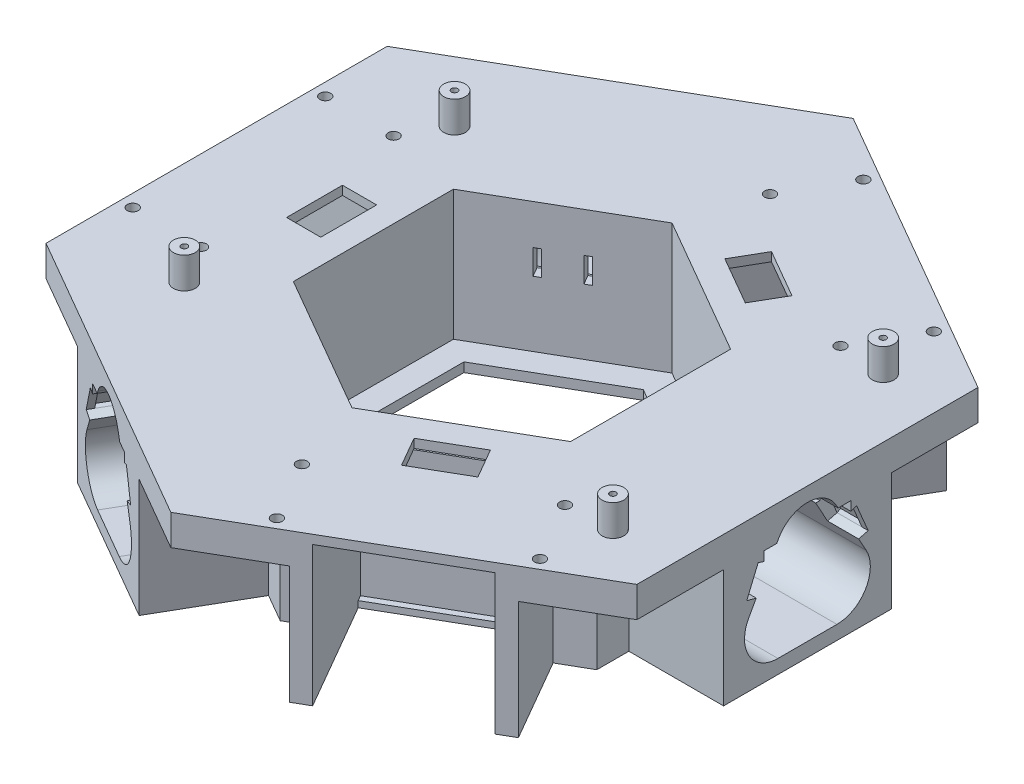
SolidWorks part; units mm, degrees
ref_plane "Plano frontal" through (0, 0, 0) normal (0, 0, 1) x (1, 0, 0)
ref_plane "Plano superior" through (0, 0, 0) normal (0, 1, 0) x (1, 0, 0)
ref_plane "Plano direito" through (0, 0, 0) normal (1, 0, 0) x (0, 0, -1)
sketch "Esboço1" plane through (0, 0, 0) normal (0, 1, 0) x (1, 0, 0)
  line L6 (-95.12, 54.9176) -> (-95.12, -54.9176)
  line L7 (95.12, 54.9176) -> (95.12, -54.9176)
  line L8 (-95.12, 54.9176) -> (0, 109.8351)
  line L9 (0, -109.8351) -> (95.12, -54.9176)
  line L10 (0, -109.8351) -> (-95.12, -54.9176)
  line L11 (95.12, 54.9176) -> (0, 109.8351)
extrude "Ressalto-extrusão1" add sketch "Esboço1" along normal blind 47.85 contours L6 L10 L9 L7 L11 L8
sketch "Esboço2" plane through (0, 47.85, 0) normal (0, 1, 0) x (1, 0, 0)
  line L6 (-36.62, 21.1426) -> (-36.62, -21.1426)
  line L7 (36.62, 21.1426) -> (36.62, -21.1426)
  line L8 (0, -42.2851) -> (36.62, -21.1426)
  line L9 (-36.62, 21.1426) -> (0, 42.2851)
  line L10 (36.62, 21.1426) -> (0, 42.2851)
  line L11 (0, -42.2851) -> (-36.62, -21.1426)
extrude "Corte-extrusão1" cut sketch "Esboço2" against normal through all
sketch "Esboço3" plane through (0, 47.85, 0) normal (0, 1, 0) x (1, 0, 0)
  line L1 (44.62, 25.7614) -> (44.62, -25.7614)
  line L3 (0, -51.5227) -> (-44.62, -25.7614)
  line L5 (44.62, -25.7614) -> (0, -51.5227)
  line L7 (-44.62, -25.7614) -> (-44.62, 25.7614)
  line L9 (-44.62, 25.7614) -> (0, 51.5227)
  line L11 (0, 51.5227) -> (44.62, 25.7614)
extrude "Corte-extrusão2" cut sketch "Esboço3" against normal blind 41.85 contours L11 L1 L5 L3 L7 L9
sketch "Esboço4" plane through (0, 0, 0) normal (0, -1, 0) x (-1, 0, 0)
  line L1 (-44.62, -25.7614) -> (-44.62, 25.7614)
  line L3 (0, 51.5227) -> (44.62, 25.7614)
  line L5 (44.62, 25.7614) -> (44.62, -25.7614)
  line L7 (44.62, -25.7614) -> (0, -51.5227)
  line L9 (-44.62, 25.7614) -> (0, 51.5227)
  line L11 (0, -51.5227) -> (-44.62, -25.7614)
extrude "Corte-extrusão3" cut sketch "Esboço4" against normal blind 3 contours L1 L9 L3 L5 L7 L11
sketch "Esboço5" plane through (-95.12, 0, 0) normal (-1, 0, 0) x (0, 0, 1)
  line L1 (0, 45) -> (-21.5, 45)
  line L2 (0, 45) -> (21.5, 45)
  line L3 (-21.5, 45) -> (-21.5, 0)
  line L4 (-54.9176, 0) -> (54.9176, 0) construction
  line L5 (21.5, 45) -> (21.5, 0)
  line L6 (-21.5, 0) -> (21.5, 0)
extrude "Corte-extrusão4" cut sketch "Esboço5" against normal blind 42.04
sketch "Esboço6" plane through (-53.08, 0, 0) normal (-1, 0, 0) x (0, 0, 1)
  line L0 (0, 0) -> (21.5, 0)
  line L1 (-21.5, 0) -> (21.5, 0) construction
  line L2 (21.5, 0) -> (21.5, 2)
  line L3 (21.5, 0) -> (21.5, 45) construction
  line L4 (0, 0) -> (-21.5, 0)
  line L5 (-21.5, 0) -> (-21.5, 2)
  line L6 (-21.5, 45) -> (-21.5, 0) construction
  line L7 (-21.5, 2) -> (21.5, 2)
extrude "Ressalto-extrusão2" add sketch "Esboço6" along normal blind 2
sketch "Esboço7" plane through (47.56, 0, -82.3763) normal (0.5, 0, -0.866) x (-0.866, 0, -0.5)
  line L1 (0, 45) -> (21.5, 45)
  line L2 (21.5, 45) -> (21.5, 0)
  line L3 (-54.9176, 0) -> (54.9176, 0) construction
  line L4 (0, 45) -> (-21.5, 45)
  line L5 (-21.5, 45) -> (-21.5, 0)
  line L6 (-21.5, 0) -> (21.5, 0)
extrude "Corte-extrusão5" cut sketch "Esboço7" against normal blind 42.04 contours L4 L5 L6 L2 L1
sketch "Esboço8" plane through (47.56, 0, 82.3763) normal (0.5, 0, 0.866) x (0.866, 0, -0.5)
  line L1 (0, 45) -> (21.5, 45)
  line L2 (21.5, 45) -> (21.5, 0)
  line L3 (-54.9176, 0) -> (54.9176, 0) construction
  line L4 (0, 45) -> (-21.5, 45)
  line L5 (-21.5, 45) -> (-21.5, 0)
  line L6 (-21.5, 0) -> (21.5, 0)
extrude "Corte-extrusão6" cut sketch "Esboço8" against normal blind 42.04
sketch "Esboço9" plane through (26.54, 0, 45.9686) normal (0.5, 0, 0.866) x (0.866, 0, -0.5)
  line L0 (0, 0) -> (21.5, 0)
  line L1 (-21.5, 0) -> (21.5, 0) construction
  line L2 (21.5, 0) -> (21.5, 2)
  line L3 (21.5, 0) -> (21.5, 45) construction
  line L4 (0, 0) -> (-21.5, 0)
  line L5 (-21.5, 0) -> (-21.5, 2)
  line L6 (-21.5, 45) -> (-21.5, 0) construction
  line L7 (-21.5, 2) -> (21.5, 2)
extrude "Ressalto-extrusão3" add sketch "Esboço9" along normal blind 2
sketch "Esboço10" plane through (26.54, 0, -45.9686) normal (0.5, 0, -0.866) x (-0.866, 0, -0.5)
  line L0 (0, 0) -> (21.5, 0)
  line L1 (-21.5, 0) -> (21.5, 0) construction
  line L2 (21.5, 0) -> (21.5, 2)
  line L3 (21.5, 45) -> (21.5, 0) construction
  line L4 (0, 0) -> (-21.5, 0)
  line L5 (-21.5, 0) -> (-21.5, 2)
  line L6 (-21.5, 45) -> (-21.5, 0) construction
  line L7 (-21.5, 2) -> (21.5, 2)
extrude "Ressalto-extrusão4" add sketch "Esboço10" along normal blind 2
sketch "Esboço11" plane through (0, 47.85, 0) normal (0, 1, 0) x (1, 0, 0)
  line L1 (-52.58, 0) -> (-52.58, 9)
  line L2 (-52.58, 9) -> (-63.58, 9)
  line L3 (-63.58, 9) -> (-63.58, -9)
  line L4 (-63.58, -9) -> (-52.58, -9)
  line L5 (-52.58, -9) -> (-52.58, 0)
  line L7 (26.29, 45.5356) -> (34.0842, 41.0356)
  line L8 (34.0842, 41.0356) -> (39.5842, 50.5619)
  line L9 (39.5842, 50.5619) -> (23.9958, 59.5619)
  line L10 (23.9958, 59.5619) -> (18.4958, 50.0356)
  line L11 (18.4958, 50.0356) -> (26.29, 45.5356)
  line L13 (26.29, -45.5356) -> (18.4958, -50.0356)
  line L14 (18.4958, -50.0356) -> (23.9958, -59.5619)
  line L15 (23.9958, -59.5619) -> (39.5842, -50.5619)
  line L16 (39.5842, -50.5619) -> (34.0842, -41.0356)
  line L17 (34.0842, -41.0356) -> (26.29, -45.5356)
extrude "Corte-extrusão7" cut sketch "Esboço11" against normal blind 2.85
sketch "Esboço12" plane through (95.12, 0, 0) normal (1, 0, 0) x (0, 0, -1)
  line L10 (-9.3154, 37.762) -> (-18.9028, 20.4605)
  line L11 (9.3154, 37.762) -> (18.9028, 20.4605)
  line L12 (-9.5, 4.5) -> (9.5, 4.5)
  arc A1 (-18.9028, 20.4605) -> (-9.5, 4.5) centre (-9.5, 15.25) ccw
  arc A3 (9.3154, 37.762) -> (-9.3154, 37.762) centre (0, 32.6) ccw
  arc A4 (9.5, 4.5) -> (18.9028, 20.4605) centre (9.5, 15.25) ccw
extrude "Corte-extrusão8" cut sketch "Esboço12" against normal blind 37.5 contours L10 A1 L12 A4 L11 A3
sketch "Esboço13" plane through (-47.56, 0, 82.3763) normal (-0.5, 0, 0.866) x (0.866, 0, 0.5)
  line L2 (-9.3154, 37.762) -> (-18.9028, 20.4605)
  line L4 (9.5, 4.5) -> (-9.5, 4.5)
  line L6 (9.3154, 37.762) -> (18.9028, 20.4605)
  arc A0 (9.3154, 37.762) -> (-9.3154, 37.762) centre (0, 32.6) ccw
  arc A1 (-18.9028, 20.4605) -> (-9.5, 4.5) centre (-9.5, 15.25) ccw
  arc A2 (9.5, 4.5) -> (18.9028, 20.4605) centre (9.5, 15.25) ccw
extrude "Corte-extrusão9" cut sketch "Esboço13" against normal blind 37.5
sketch "Esboço14" plane through (-47.56, 0, -82.3763) normal (-0.5, 0, -0.866) x (-0.866, 0, 0.5)
  line L0 (-9.3154, 37.762) -> (-18.9028, 20.4605)
  line L2 (9.3154, 37.762) -> (18.9028, 20.4605)
  line L4 (9.5, 4.5) -> (-9.5, 4.5)
  arc A0 (9.3154, 37.762) -> (-9.3154, 37.762) centre (0, 32.6) ccw
  arc A1 (-18.9028, 20.4605) -> (-9.5, 4.5) centre (-9.5, 15.25) ccw
  arc A2 (9.5, 4.5) -> (18.9028, 20.4605) centre (9.5, 15.25) ccw
extrude "Corte-extrusão10" cut sketch "Esboço14" against normal blind 37.5
sketch "Esboço15" plane through (95.12, 0, 0) normal (1, 0, 0) x (0, 0, -1)
  line L15 (-9.3154, 37.762) -> (-18.8809, 20.5)
  line L16 (9.3154, 37.762) -> (18.8809, 20.5)
  line L19 (-18.8809, 20.5) -> (18.8809, 20.5)
  arc A0 (9.3154, 37.762) -> (-9.3154, 37.762) centre (0, 32.6) ccw
extrude "Corte-extrusão11" cut sketch "Esboço15" against normal blind 47
sketch "Esboço16" plane through (-47.56, 0, -82.3763) normal (-0.5, 0, -0.866) x (-0.866, 0, 0.5)
  line L2 (9.3154, 37.762) -> (18.9028, 20.4605)
  line L3 (-9.3154, 37.762) -> (-18.9028, 20.4605)
  line L17 (18.8808, 20.5) -> (-18.8808, 20.5)
  arc A1 (-18.8808, 20.5) -> (-18.9028, 20.4605) centre (-9.5, 15.25) ccw
  arc A2 (18.9028, 20.4605) -> (18.8808, 20.5) centre (9.5, 15.25) ccw
  arc A5 (9.3154, 37.762) -> (-9.3154, 37.762) centre (0, 32.6) ccw
extrude "Corte-extrusão12" cut sketch "Esboço16" against normal blind 47 contours L3 A1 L17 A2 L2 A5
sketch "Esboço17" plane through (-47.56, 0, 82.3763) normal (-0.5, 0, 0.866) x (0.866, 0, 0.5)
  line L16 (-9.3154, 37.762) -> (-18.8809, 20.5)
  line L17 (9.3154, 37.762) -> (18.8809, 20.5)
  line L18 (18.8809, 20.5) -> (-18.8809, 20.5)
  arc A2 (9.3154, 37.762) -> (-9.3154, 37.762) centre (0, 32.6) ccw
extrude "Corte-extrusão13" cut sketch "Esboço17" against normal blind 47
sketch "Esboço22" plane through (95.12, 0, 0) normal (1, 0, 0) x (0, 0, -1)
  line L3 (14, 36.75) -> (-14, 36.75)
  line L4 (14, 31.75) -> (-14, 31.75)
  line L8 (14, 36.75) -> (14, 31.75)
  line L10 (-14, 36.75) -> (-14, 31.75)
extrude "Corte-extrusão17" cut sketch "Esboço22" against normal blind 47
sketch "Esboço23" plane through (-47.56, 0, -82.3763) normal (-0.5, 0, -0.866) x (-0.866, 0, 0.5)
  line L3 (14, 36.75) -> (-14, 36.75)
  line L4 (14, 31.75) -> (-14, 31.75)
  line L8 (14, 36.75) -> (14, 31.75)
  line L10 (-14, 36.75) -> (-14, 31.75)
extrude "Corte-extrusão18" cut sketch "Esboço23" against normal blind 47
sketch "Esboço24" plane through (-47.56, 0, 82.3763) normal (-0.5, 0, 0.866) x (0.866, 0, 0.5)
  line L3 (14, 36.75) -> (-14, 36.75)
  line L4 (14, 31.75) -> (-14, 31.75)
  line L8 (14, 36.75) -> (14, 31.75)
  line L10 (-14, 36.75) -> (-14, 31.75)
extrude "Corte-extrusão19" cut sketch "Esboço24" against normal blind 47
sketch "Esboço25" plane through (95.12, 0, 0) normal (1, 0, 0) x (0, 0, -1)
  line L3 (-18.8809, 20.5) -> (18.8809, 20.5) construction
  line L22 (-15.86, 34.37) -> (0, 29.25)
  line L23 (15.86, 34.37) -> (0, 29.25)
  line L24 (-19.55, 25.62) -> (0, 20.5)
  line L25 (0, 20.5) -> (19.55, 25.62)
  line L26 (19.55, 25.62) -> (15.86, 34.37)
  line L27 (-15.86, 34.37) -> (-19.55, 25.62)
extrude "Corte-extrusão20" cut sketch "Esboço25" against normal blind 10
sketch "Esboço26" plane through (-47.56, 0, -82.3763) normal (-0.5, 0, -0.866) x (-0.866, 0, 0.5)
  line L19 (18.8808, 20.5) -> (-18.8808, 20.5) construction
  line L20 (-15.86, 34.37) -> (0, 29.25)
  line L21 (0, 29.25) -> (15.86, 34.37)
  line L22 (-19.55, 25.62) -> (-15.86, 34.37)
  line L23 (-19.55, 25.62) -> (0, 20.5)
  line L24 (0, 20.5) -> (19.55, 25.62)
  line L25 (15.86, 34.37) -> (19.55, 25.62)
extrude "Corte-extrusão21" cut sketch "Esboço26" against normal blind 10 contours L23 L24 L25 L21 L20 L22
sketch "Esboço27" plane through (-47.56, 0, 82.3763) normal (-0.5, 0, 0.866) x (0.866, 0, 0.5)
  line L3 (-15.86, 34.37) -> (0, 29.25)
  line L4 (0, 29.25) -> (15.86, 34.37)
  line L5 (-19.55, 25.62) -> (-15.86, 34.37)
  line L6 (-19.55, 25.62) -> (0, 20.5)
  line L7 (0, 20.5) -> (19.55, 25.62)
  line L8 (15.86, 34.37) -> (19.55, 25.62)
extrude "Corte-extrusão22" cut sketch "Esboço27" against normal blind 10 contours L6 L5 L3 L4 L8 L7
sketch "Esboço28" plane through (22.3184, 10.868, -12.8856) normal (-0.798, -0.3886, 0.4607) x (0.4142, 0.2017, 0.8876)
  line L1 (-79.5509, 34.2548) -> (-89.3084, 36.4438) construction
  line L2 (-87.3569, 36.006) -> (-85.2781, 45.2719)
  line L3 (-77.4722, 43.5207) -> (-87.2296, 45.7097) construction
  line L4 (-85.2781, 45.2719) -> (-77.4722, 43.5207)
  line L5 (-77.4722, 43.5207) -> (-79.5509, 34.2548)
  line L7 (-87.3569, 36.006) -> (-79.5509, 34.2548)
extrude "Corte-extrusão23" cut sketch "Esboço28" against normal blind 1.5 draft 15 contours L5 L7 L2 L4 draft outward yes
sketch "Esboço29" plane through (-22.3184, 10.868, 12.8856) normal (0.798, -0.3886, -0.4607) x (-0.4142, 0.2017, -0.8876)
  line L1 (86.5602, -3.0112) -> (96.3177, -5.2002) construction
  line L2 (94.3662, -4.7624) -> (86.5602, -3.0112)
  line L3 (86.5602, -3.0112) -> (88.639, 6.2547)
  line L4 (88.639, 6.2547) -> (98.3964, 4.0657) construction
  line L5 (88.639, 6.2547) -> (86.5602, -3.0112) construction
  line L6 (88.639, 6.2547) -> (96.4449, 4.5035)
  line L7 (96.4449, 4.5035) -> (94.3662, -4.7624)
extrude "Corte-extrusão24" cut sketch "Esboço29" against normal blind 1.5 draft 15 contours L2 L3 L6 L7 draft outward yes
sketch "Esboço30" plane through (-22.3184, 10.868, -12.8856) normal (0.798, -0.3886, 0.4607) x (0.4142, -0.2017, -0.8876)
  line L1 (-86.5602, -3.0112) -> (-96.3177, -5.2002) construction
  line L2 (-94.3662, -4.7624) -> (-86.5602, -3.0112)
  line L3 (-86.5602, -3.0112) -> (-88.639, 6.2547)
  line L4 (-88.639, 6.2547) -> (-96.4449, 4.5035)
  line L5 (-88.639, 6.2547) -> (-98.3964, 4.0657) construction
  line L6 (-96.4449, 4.5035) -> (-94.3662, -4.7624)
extrude "Corte-extrusão25" cut sketch "Esboço30" against normal blind 1.5 draft 15 draft outward yes
sketch "Esboço31" plane through (22.3184, 10.868, 12.8856) normal (-0.798, -0.3886, -0.4607) x (-0.4142, -0.2017, 0.8876)
  line L1 (77.4722, 43.5207) -> (87.2296, 45.7097) construction
  line L2 (85.2781, 45.2719) -> (77.4722, 43.5207)
  line L3 (77.4722, 43.5207) -> (79.5509, 34.2548)
  line L4 (79.5509, 34.2548) -> (87.3569, 36.006)
  line L5 (79.5509, 34.2548) -> (89.3084, 36.4438) construction
  line L6 (87.3569, 36.006) -> (85.2781, 45.2719)
extrude "Corte-extrusão26" cut sketch "Esboço31" against normal blind 1.5 draft 15 draft outward yes
sketch "Esboço32" plane through (0, 10.868, -25.7711) normal (0, -0.3886, 0.9214) x (1, 0, 0)
  line L1 (85.12, 16.0101) -> (95.12, 16.0101) construction
  line L2 (93.12, 16.0101) -> (85.12, 16.0101)
  line L3 (85.12, 16.0101) -> (85.12, 25.5063)
  line L4 (85.12, 25.5063) -> (93.12, 25.5063)
  line L5 (85.12, 25.5063) -> (95.12, 25.5063) construction
  line L6 (93.12, 25.5063) -> (93.12, 16.0101)
extrude "Corte-extrusão27" cut sketch "Esboço32" against normal blind 1.5 draft 15 draft outward yes
sketch "Esboço33" plane through (0, 10.868, 25.7711) normal (0, -0.3886, -0.9214) x (-1, 0, 0)
  line L0 (-85.12, 16.0101) -> (-93.12, 16.0101)
  line L1 (-85.12, 16.0101) -> (-95.12, 16.0101) construction
  line L2 (-93.12, 16.0101) -> (-93.12, 25.5063)
  line L3 (-85.12, 25.5063) -> (-95.12, 25.5063) construction
  line L4 (-93.12, 25.5063) -> (-85.12, 25.5063)
  line L5 (-85.12, 25.5063) -> (-85.12, 16.0101)
extrude "Corte-extrusão28" cut sketch "Esboço33" against normal blind 1.5 draft 15 draft outward yes
sketch "Esboço34" plane through (95.12, 0, 0) normal (1, 0, 0) x (0, 0, -1)
  line L3 (-5, 27) -> (-5, 35)
  line L4 (-5, 35) -> (-7, 35)
  line L5 (-7, 35) -> (-7, 27)
  line L6 (-7, 27) -> (-5, 27)
  line L8 (5, 27) -> (5, 35)
  line L9 (5, 35) -> (7, 35)
  line L10 (7, 35) -> (7, 27)
  line L11 (5, 27) -> (7, 27)
extrude "Corte-extrusão29" cut sketch "Esboço34" against normal blind 78.5
sketch "Esboço35" plane through (-47.56, 0, -82.3763) normal (-0.5, 0, -0.866) x (-0.866, 0, 0.5)
  line L4 (-5, 27) -> (-5, 35)
  line L5 (-5, 35) -> (-7, 35)
  line L6 (-7, 35) -> (-7, 27)
  line L7 (-7, 27) -> (-5, 27)
  line L9 (5, 27) -> (5, 35)
  line L10 (5, 35) -> (7, 35)
  line L11 (7, 35) -> (7, 27)
  line L12 (5, 27) -> (7, 27)
extrude "Corte-extrusão30" cut sketch "Esboço35" against normal blind 78.5
sketch "Esboço36" plane through (-47.56, 0, 82.3763) normal (-0.5, 0, 0.866) x (0.866, 0, 0.5)
  line L4 (-5, 27) -> (-5, 35)
  line L5 (-5, 35) -> (-7, 35)
  line L6 (-7, 35) -> (-7, 27)
  line L7 (-7, 27) -> (-5, 27)
  line L9 (5, 27) -> (5, 35)
  line L10 (5, 35) -> (7, 35)
  line L11 (7, 35) -> (7, 27)
  line L12 (5, 27) -> (7, 27)
extrude "Corte-extrusão31" cut sketch "Esboço36" against normal blind 78.5
sketch "Esboço38" plane through (0, 0, 0) normal (0, -1, 0) x (-1, 0, 0)
  line L30 (-8.9273, 69.4626) -> (0, 74.6167)
  line L32 (8.9273, 69.4626) -> (0, 74.6167)
  line L46 (64.62, 27) -> (64.62, 37.3084)
  line L47 (126.8267, 27) -> (126.8267, -27)
  line L58 (55.6927, 42.4626) -> (64.62, 37.3084)
  line L61 (64.62, -27) -> (64.62, -37.3084)
  line L64 (8.9273, -69.4626) -> (0, -74.6167)
  line L67 (-55.6927, -42.4626) -> (-64.62, -37.3084)
  line L70 (-64.62, 27) -> (-64.62, 37.3084)
  line L72 (55.6927, -42.4626) -> (64.62, -37.3084)
  line L73 (86.796, -96.3351) -> (40.0306, -123.3351)
  line L74 (-8.9273, -69.4626) -> (0, -74.6167)
  line L75 (-40.0306, -123.3351) -> (-86.796, -96.3351)
  line L76 (-64.62, -27) -> (-64.62, -37.3084)
  line L77 (-40.0306, -123.3351) -> (-8.9273, -69.4626)
  line L78 (-86.796, -96.3351) -> (-55.6927, -42.4626)
  line L79 (-40.0306, 123.3351) -> (-86.796, 96.3351)
  line L80 (-55.6927, 42.4626) -> (-64.62, 37.3084)
  line L81 (-126.8267, 27) -> (-126.8267, -27)
  line L82 (86.796, 96.3351) -> (144.1652, 53.1986)
  line L83 (-86.796, 96.3351) -> (-55.6927, 42.4626)
  line L84 (-40.0306, 123.3351) -> (-8.9273, 69.4626)
  line L85 (144.1652, 53.1986) -> (157.5659, 0)
  line L87 (157.5659, 0) -> (144.1652, -63.213)
  line L88 (-126.8267, -27) -> (-64.62, -27)
  line L89 (-126.8267, 27) -> (-64.62, 27)
  line L90 (144.1652, -63.213) -> (119.6711, -105.6381)
  line L91 (119.6711, -105.6381) -> (86.796, -138.7939)
  line L92 (86.796, -138.7939) -> (8.9273, -147.887)
  line L93 (126.8267, 27) -> (64.62, 27)
  line L94 (126.8267, -27) -> (64.62, -27)
  line L95 (8.9273, -147.887) -> (-79.3373, -147.887)
  line L96 (-79.3373, -147.887) -> (-101.3016, -126.1087)
  line L97 (-101.3016, -126.1087) -> (-135.3677, -74.6167)
  line L98 (40.0306, 123.3351) -> (8.9273, 69.4626)
  line L99 (86.796, 96.3351) -> (55.6927, 42.4626)
  line L100 (-135.3677, -74.6167) -> (-152.3432, -27)
  line L101 (-152.3432, -27) -> (-152.3432, 37.3084)
  line L102 (-152.3432, 37.3084) -> (-101.3016, 133.3327)
  line L103 (86.796, -96.3351) -> (55.6927, -42.4626)
  line L104 (40.0306, -123.3351) -> (8.9273, -69.4626)
  line L105 (-101.3016, 133.3327) -> (-48.9949, 151.9802)
  line L106 (-48.9949, 151.9802) -> (18.3094, 159.8396)
  line L107 (18.3094, 159.8396) -> (40.0306, 123.3351)
extrude "Corte-extrusão37" cut sketch "Esboço38" against normal blind 38
sketch "Esboço42" plane through (0, 47.85, 0) normal (0, 1, 0) x (1, 0, 0)
  circle A0 centre (18.7132, 94.4122) radius 1.75
  circle A1 centre (61.4068, -44.3597) radius 1.75
  circle A2 centre (-91.12, 31) radius 1.75
  circle A3 centre (18.7132, -94.4122) radius 1.75
  circle A5 centre (-91.12, -31) radius 1.75
  circle A6 centre (7.7132, -75.3597) radius 1.75
  circle A7 centre (72.4068, -63.4122) radius 1.75
  circle A9 centre (-69.12, 31) radius 1.75
  circle A10 centre (61.4068, 44.3597) radius 1.75
  circle A12 centre (7.7132, 75.3597) radius 1.75
  circle A13 centre (-69.12, -31) radius 1.75
  circle A14 centre (72.4068, 63.4122) radius 1.75
extrude "Corte-extrusão38" cut sketch "Esboço42" against normal through all
sketch "Esboço43" plane through (0, 47.85, 0) normal (0, 1, 0) x (1, 0, 0)
  circle A0 centre (-62, 43.5) radius 3.5
  circle A1 centre (76, 43.5) radius 3.5
  circle A2 centre (-62, -43.5) radius 3.5
  circle A3 centre (76, -43.5) radius 3.5
extrude "Ressalto-extrusão5" add sketch "Esboço43" along normal blind 10
sketch "Esboço44" plane through (0, 57.85, 0) normal (0, 1, 0) x (1, 0, 0)
  circle A0 centre (-62, 43.5) radius 1
  circle A1 centre (-62, -43.5) radius 1
  circle A2 centre (76, -43.5) radius 1
  circle A3 centre (76, 43.5) radius 1
extrude "Corte-extrusão39" cut sketch "Esboço44" against normal blind 6
